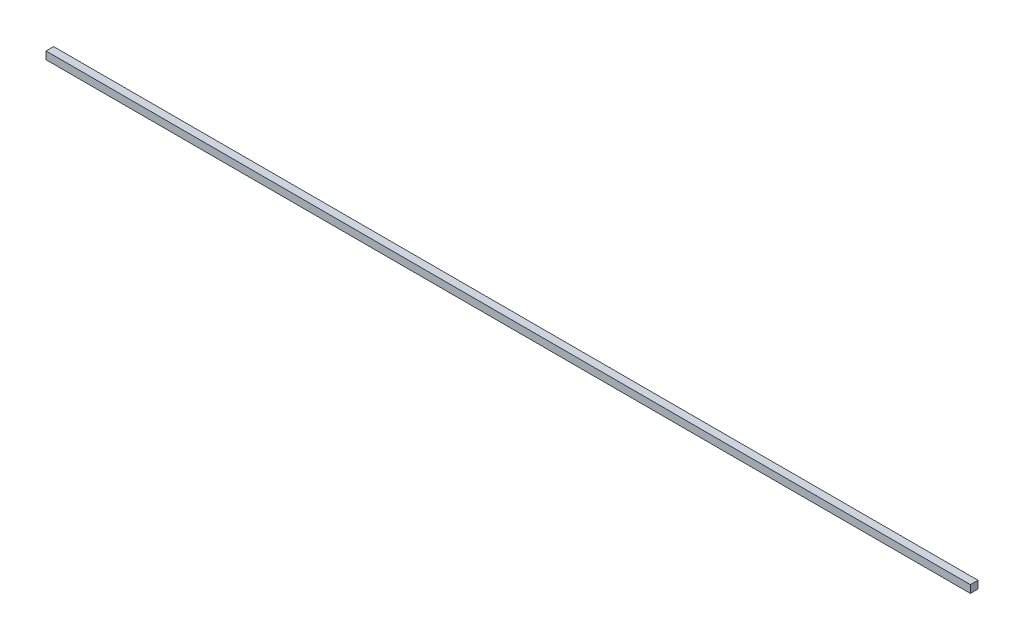
SolidWorks part; units mm, degrees
ref_plane "Front Plane" through (0, 0, 0) normal (0, 0, 1) x (1, 0, 0)
ref_plane "Top Plane" through (0, 0, 0) normal (0, 1, 0) x (1, 0, 0)
ref_plane "Right Plane" through (0, 0, 0) normal (1, 0, 0) x (0, 0, -1)
sketch "Sketch1" plane through (0, 0, 0) normal (0, 1, 0) x (1, 0, 0)
  line L1 (121.5, -1) -> (-121.5, -1)
  line L2 (121.5, -1) -> (121.5, 1)
  line L3 (121.5, 1) -> (-121.5, 1)
  line L4 (-121.5, -1) -> (-121.5, 1)
  line L5 (121.5, -1) -> (-121.5, 1) construction
  line L6 (121.5, 1) -> (-121.5, -1) construction
  point P0 (0, 0)
  dimension "D1" = 2
  dimension "D2" = 243
extrude "Boss-Extrude1" add sketch "Sketch1" along normal blind 2
